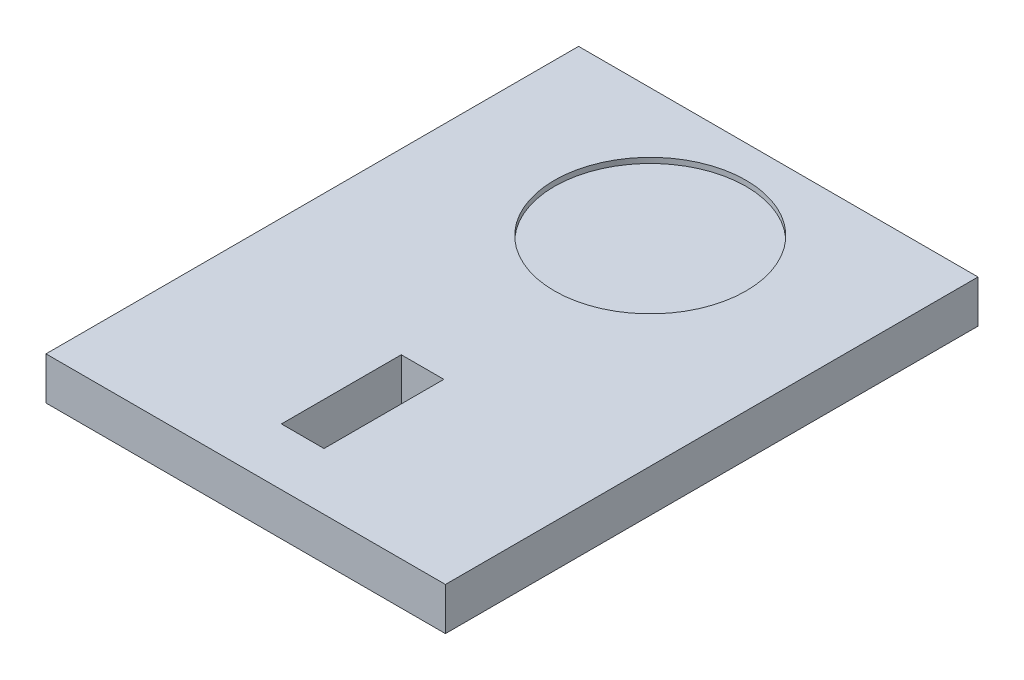
SolidWorks part; units mm, degrees
ref_plane "Ön Düzlem" through (0, 0, 0) normal (0, 0, 1) x (1, 0, 0)
ref_plane "Üst Düzlem" through (0, 0, 0) normal (0, 1, 0) x (1, 0, 0)
ref_plane "Sağ Düzlem" through (0, 0, 0) normal (1, 0, 0) x (0, 0, -1)
sketch "Çizim1" plane through (0, 0, 0) normal (0, 1, 0) x (1, 0, 0)
  line L0 (-57.9843, 182.4607) -> (-57.9843, -17.5393) construction
  line L1 (-132.9843, 182.4607) -> (17.0157, 182.4607)
  line L2 (-132.9843, 182.4607) -> (-132.9843, -17.5393)
  line L3 (-132.9843, -17.5393) -> (17.0157, -17.5393)
  line L4 (17.0157, 182.4607) -> (17.0157, -17.5393)
  line L5 (-132.9843, 182.4607) -> (17.0157, -17.5393) construction
  line L6 (-132.9843, -17.5393) -> (17.0157, 182.4607) construction
  point P0 (-57.9843, 82.4607)
  dimension "D1" = 200
  dimension "D2" = 150
extrude "Yükseklik-Ekstrüzyon1" add sketch "Çizim1" along normal blind 16
sketch "Çizim2" plane through (0, 16, 0) normal (0, 1, 0) x (1, 0, 0)
  line L0 (-57.9843, -17.5393) -> (-57.9843, 182.4607) construction
  line L1 (-132.9843, -17.5393) -> (17.0157, -17.5393) construction
  line L2 (17.0157, 182.4607) -> (-132.9843, 182.4607) construction
  line L4 (-65.9843, 48.8734) -> (-49.9843, 48.8734)
  line L5 (-65.9843, 48.8734) -> (-65.9843, 3.8734)
  line L6 (-65.9843, 3.8734) -> (-49.9843, 3.8734)
  line L7 (-49.9843, 48.8734) -> (-49.9843, 3.8734)
  line L8 (-65.9843, 48.8734) -> (-49.9843, 3.8734) construction
  line L9 (-65.9843, 3.8734) -> (-49.9843, 48.8734) construction
  point P6 (-57.9843, 26.3734)
  dimension "D1" = 45
  dimension "D2" = 16
extrude "Kes-Ekstrüzyon1" cut sketch "Çizim2" against normal blind 29
sketch "Çizim3" plane through (0, 16, 0) normal (0, 1, 0) x (1, 0, 0)
  line L0 (-57.9843, 182.4607) -> (-57.9843, -17.5393) construction
  line L1 (17.0157, 182.4607) -> (-132.9843, 182.4607) construction
  line L2 (-132.9843, -17.5393) -> (17.0157, -17.5393) construction
  circle A0 centre (-57.9843, 134.3771) radius 40
  circle A1 centre (-57.9843, 134.3771) radius 36
  dimension "D1" = 80
  dimension "D2" = 72
extrude "Kes-Ekstrüzyon3" cut sketch "Çizim3" against normal blind 2 contours A1
